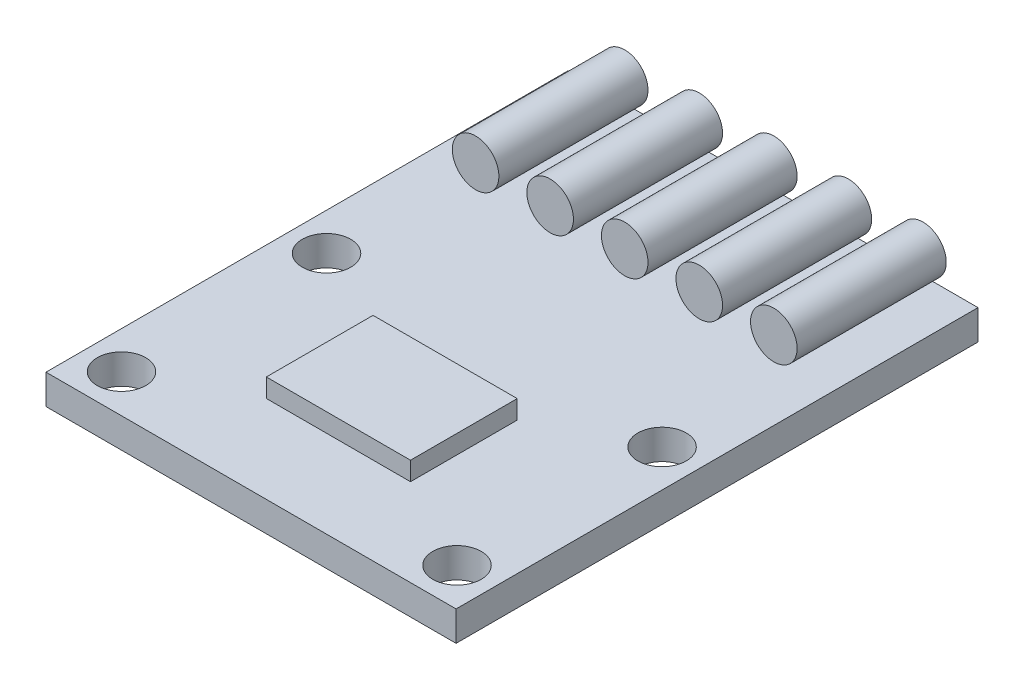
SolidWorks part; units mm, degrees
ref_plane "Front" through (0, 0, 0) normal (0, 0, 1) x (1, 0, 0)
ref_plane "Top" through (0, 0, 0) normal (0, 1, 0) x (1, 0, 0)
ref_plane "Right" through (0, 0, 0) normal (1, 0, 0) x (0, 0, -1)
sketch "Sketch1" plane through (0, 0, 0) normal (0, 1, 0) x (1, 0, 0)
  line L1 (-11, 14) -> (11, 14)
  line L2 (-11, 14) -> (-11, -14)
  line L3 (-11, -14) -> (11, -14)
  line L4 (11, 14) -> (11, -14)
  line L5 (-11, 14) -> (11, -14) construction
  line L6 (-11, -14) -> (11, 14) construction
  point P0 (0, 0)
  dimension "D1" = 22
  dimension "D2" = 28
extrude "Boss-Extrude1" add sketch "Sketch1" along normal blind 1.6
sketch "Sketch3" plane through (0, 1.6, 0) normal (0, 1, 0) x (1, 0, 0)
  line L0 (-11, -14) -> (11, -14) construction
  line L1 (-9, -0.95) -> (9, -0.95) construction
  line L2 (-9, -0.95) -> (-9, -11.95) construction
  line L3 (-9, -11.95) -> (9, -11.95) construction
  line L4 (9, -0.95) -> (9, -11.95) construction
  line L5 (-9, -0.95) -> (9, -11.95) construction
  line L6 (-9, -11.95) -> (9, -0.95) construction
  circle A0 centre (9, -11.95) radius 1.3
  circle A1 centre (9, -0.95) radius 1.3
  circle A2 centre (-9, -0.95) radius 1.3
  circle A3 centre (-9, -11.95) radius 1.3
  point P0 (0, -6.45)
  point P5 (9, -13.25)
  point P13 (10.3, -11.95)
  point P15 (-10.3, -11.95)
  dimension "D3" = 2.6
  dimension "D4" = 0.75
  dimension "D1" = 18
  dimension "D2" = 11
extrude "Cut-Extrude1" cut sketch "Sketch3" against normal up to surface (1.6 mm away) up to face at (0, 0, 0)
sketch "Sketch4" plane through (0, 1.6, 0) normal (0, 1, 0) x (1, 0, 0)
  line L0 (9, -11.95) -> (-9, -0.95) construction
  line L1 (-3.8673, -3.5874) -> (3.8673, -3.5874)
  line L2 (-3.8673, -3.5874) -> (-3.8673, -9.3126)
  line L3 (-3.8673, -9.3126) -> (3.8673, -9.3126)
  line L4 (3.8673, -3.5874) -> (3.8673, -9.3126)
  line L5 (-3.8673, -3.5874) -> (3.8673, -9.3126) construction
  line L6 (-3.8673, -9.3126) -> (3.8673, -3.5874) construction
  line L7 (-9, -11.95) -> (9, -0.95) construction
  point P0 (0, -6.45)
  point P14 (0, -6.45)
extrude "Boss-Extrude2" add sketch "Sketch4" along normal blind 1
sketch "Sketch5" plane through (0, 2.6, 0) normal (0, 1, 0) x (1, 0, 0)
  line L1 (3.8673, -9.3126) -> (-3.8673, -3.5874) construction
  line L2 (3.8673, -3.5874) -> (-3.8673, -9.3126) construction
  point P0 (0, -6.45)
sketch "Sketch6" plane through (0, 0, -14) normal (0, 0, -1) x (-1, 0, 0)
  line L0 (-11, 1.6) -> (11, 1.6) construction
  circle A0 centre (7.9533, 2.85) radius 1.25
  circle A1 centre (3.9533, 2.85) radius 1.25
  circle A2 centre (-0.0467, 2.85) radius 1.25
  circle A3 centre (-4.0467, 2.85) radius 1.25
  circle A4 centre (-8.0467, 2.85) radius 1.25
  point P4 (7.9533, 3.1)
  dimension "D1" = 2.5
  dimension "D2" = 5
extrude "Boss-Extrude3" add sketch "Sketch6" against normal blind 8 separate body
